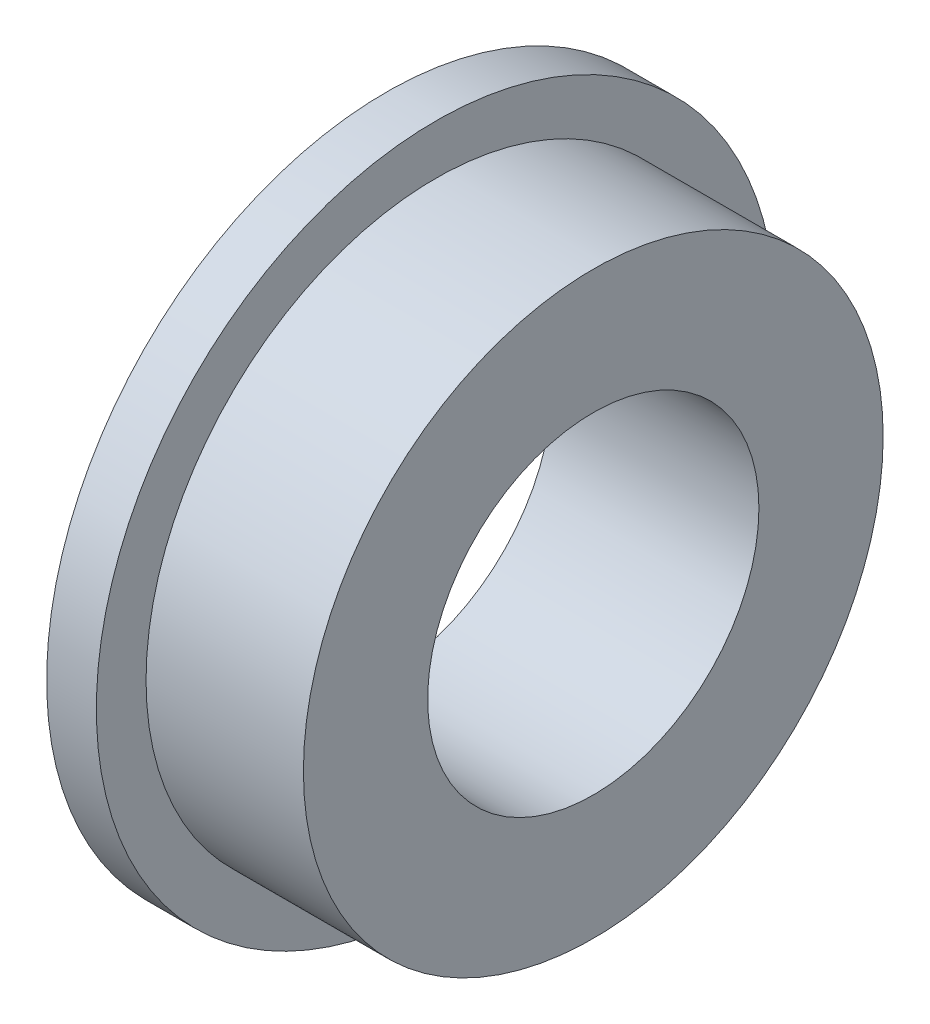
SolidWorks part; units mm, degrees
ref_plane "前视基准面" through (0, 0, 0) normal (0, 0, 1) x (1, 0, 0)
ref_plane "上视基准面" through (0, 0, 0) normal (0, 1, 0) x (1, 0, 0)
ref_plane "右视基准面" through (0, 0, 0) normal (1, 0, 0) x (0, 0, -1)
other "Configuration Table"
sketch "草图1" plane through (0, 0, 0) normal (1, 0, 0) x (0, 0, -1)
  circle A0 centre (0, 0) radius 4.1
  circle A1 centre (0, 0) radius 2
  dimension "D1" = 8.2
  dimension "D2" = 4
extrude "凸台-拉伸1" add sketch "草图1" along normal blind 2.5
sketch "草图2" plane through (2.5, 0, 0) normal (1, 0, 0) x (0, 0, -1)
  circle A0 centre (0, 0) radius 3.5
  dimension "D1" = 7
extrude "切除-拉伸1" cut sketch "草图2" against normal blind 1.9 flip side to cut
